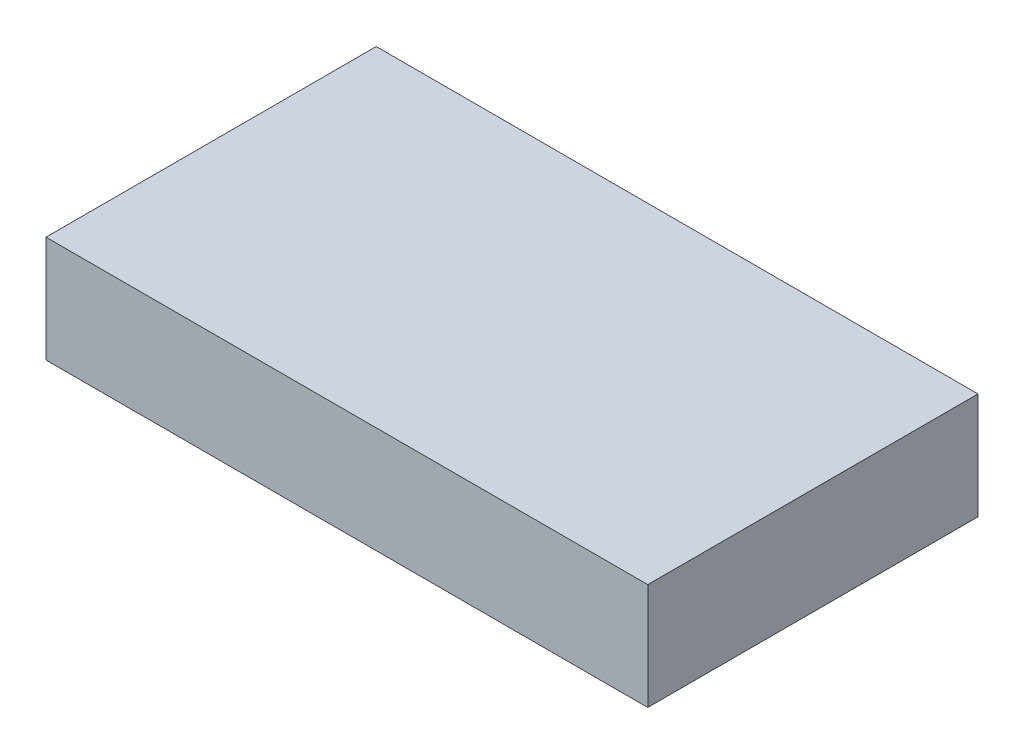
SolidWorks part; units mm, degrees
ref_plane "Front Plane" through (0, 0, 0) normal (0, 0, 1) x (1, 0, 0)
ref_plane "Top Plane" through (0, 0, 0) normal (0, 1, 0) x (1, 0, 0)
ref_plane "Right Plane" through (0, 0, 0) normal (1, 0, 0) x (0, 0, -1)
sketch "Sketch1" plane through (0, 0, 0) normal (0, 1, 0) x (1, 0, 0)
  line L0 (0, 29.4383) -> (0, -30.0127) construction
  line L1 (-20.5, -12.8134) -> (20.5, -12.8134)
  line L2 (20.5, -12.8134) -> (20.5, 9.6866)
  line L3 (20.5, 9.6866) -> (-20.5, 9.6866)
  line L4 (-20.5, -12.8134) -> (-20.5, 9.6866)
  point P8 (0, -12.8134)
  point P9 (0, 9.6866)
  dimension "D1" = 20.5
  dimension "D2" = 22.5
extrude "Boss-Extrude1" add sketch "Sketch1" along normal blind 7.25
